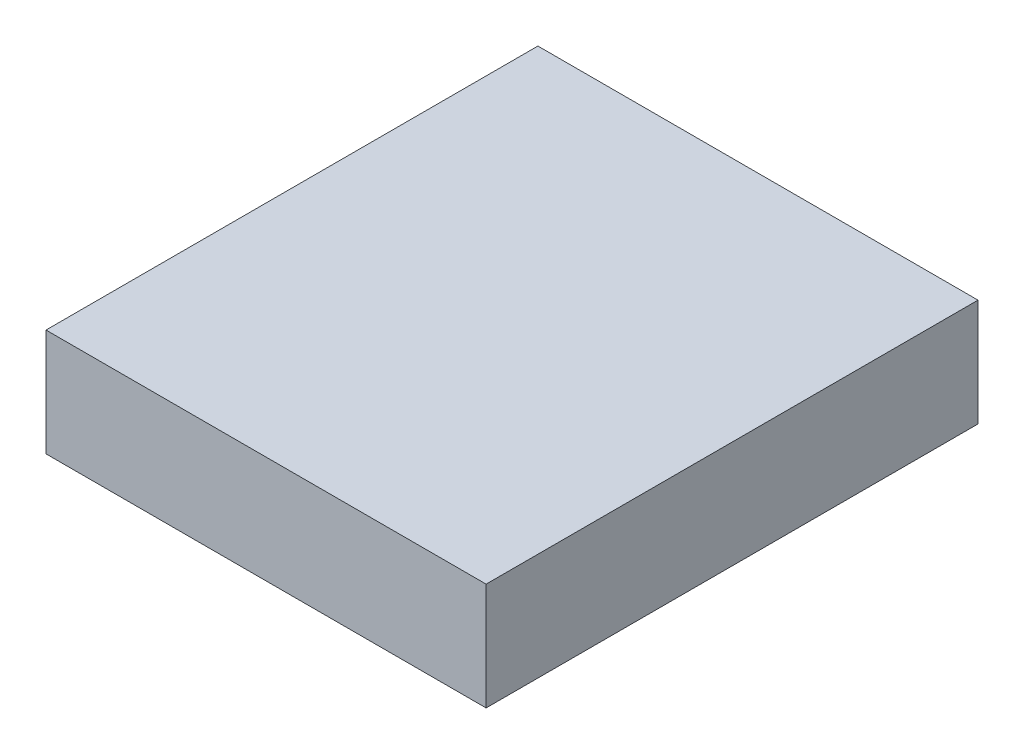
SolidWorks part; units mm, degrees
ref_plane "Front Plane" through (0, 0, 0) normal (0, 0, 1) x (1, 0, 0)
ref_plane "Top Plane" through (0, 0, 0) normal (0, 1, 0) x (1, 0, 0)
ref_plane "Right Plane" through (0, 0, 0) normal (1, 0, 0) x (0, 0, -1)
sketch "Sketch1" plane through (0, 0, 0) normal (0, 1, 0) x (1, 0, 0)
  line L0 (0, 0) -> (29.75, 0)
  line L1 (29.75, 0) -> (29.75, 33.25)
  line L2 (29.75, 33.25) -> (0, 33.25)
  line L3 (0, 33.25) -> (0, 0)
  dimension "D1" = 33.25
  dimension "D2" = 29.75
extrude "Boss-Extrude1" add sketch "Sketch1" along normal blind 7.25
